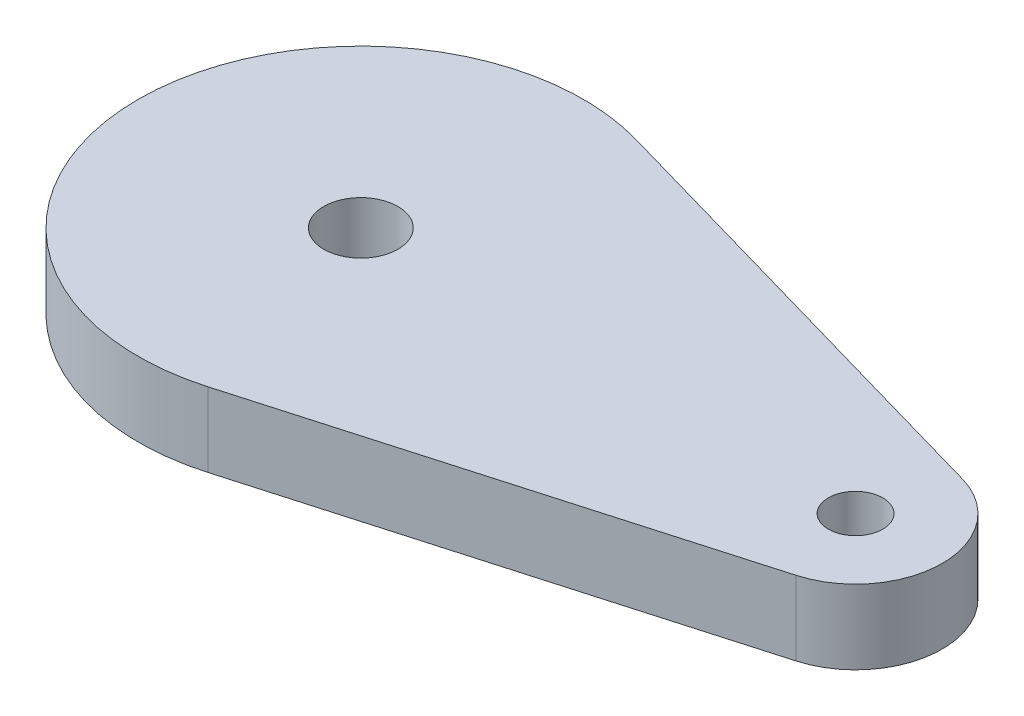
SolidWorks part; units mm, degrees
ref_plane "정면" through (0, 0, 0) normal (0, 0, 1) x (1, 0, 0)
ref_plane "윗면" through (0, 0, 0) normal (0, 1, 0) x (1, 0, 0)
ref_plane "우측면" through (0, 0, 0) normal (1, 0, 0) x (0, 0, -1)
sketch "스케치1" plane through (0, 0, 0) normal (0, 1, 0) x (1, 0, 0)
  line L0 (2.475, 8.653) -> (20.9625, 3.3651)
  line L1 (20.9625, -3.3651) -> (2.475, -8.653)
  line L2 (0, 0) -> (20, 0) construction
  arc A0 (2.475, 8.653) -> (2.475, -8.653) centre (0, 0) ccw
  arc A1 (20.9625, -3.3651) -> (20.9625, 3.3651) centre (20, 0) ccw
  dimension "D1" = 18
  dimension "D2" = 7
  dimension "D3" = 20
extrude "보스-돌출1" add sketch "스케치1" along normal blind 3
sketch "스케치2" plane through (0, 3, 0) normal (0, 1, 0) x (1, 0, 0)
  circle A0 centre (0, 0) radius 1.5
  circle A1 centre (20, 0) radius 1.1
  dimension "D1" = 3
  dimension "D2" = 2.2
extrude "컷-돌출1" cut sketch "스케치2" against normal blind 3
